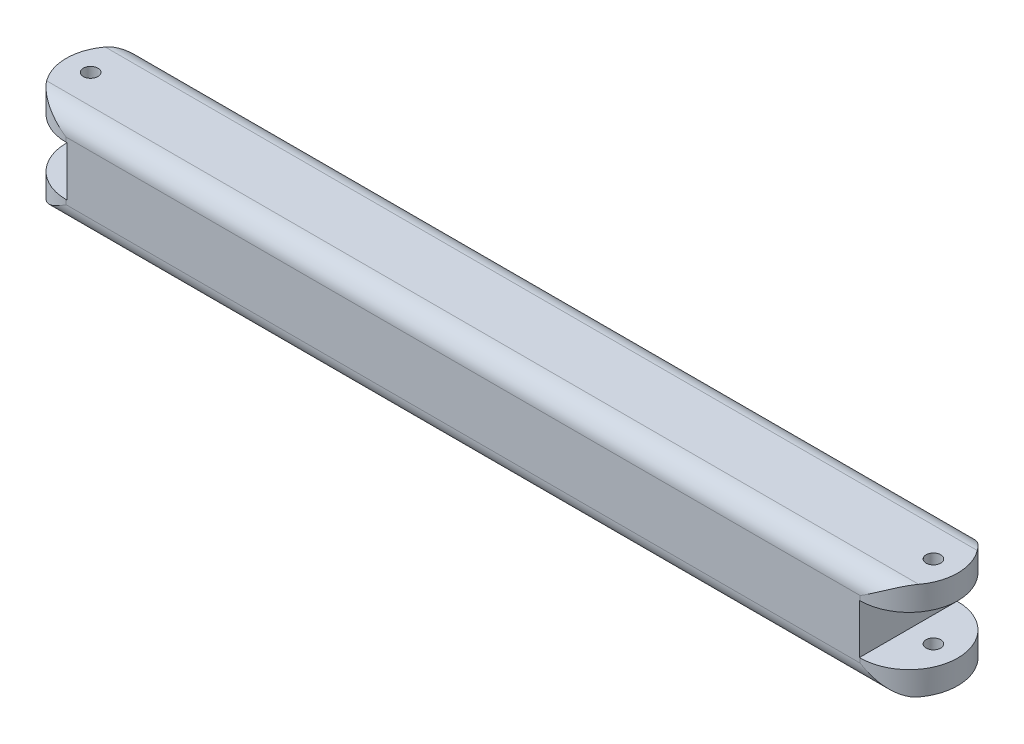
SolidWorks part; units mm, degrees
material "Custom Plastic"
ref_plane "Front Plane" through (0, 0, 0) normal (0, 0, 1) x (1, 0, 0)
ref_plane "Top Plane" through (0, 0, 0) normal (0, 1, 0) x (1, 0, 0)
ref_plane "Right Plane" through (0, 0, 0) normal (1, 0, 0) x (0, 0, -1)
sketch "Sketch1" plane through (0, 0, 0) normal (1, 0, 0) x (0, 0, -1)
  line L0 (-15, 15) -> (15, -15) construction
  line L1 (-15, 25) -> (15, 25)
  line L2 (-25, 15) -> (-25, -15)
  line L3 (-15, -25) -> (15, -25)
  line L4 (25, 15) -> (25, -15)
  arc A1 (-25, -15) -> (-15, -25) centre (-15, -15) ccw
  arc A2 (15, -25) -> (25, -15) centre (15, -15) ccw
  arc A3 (15, 25) -> (25, 15) centre (15, 15) cw
  arc A4 (-15, 25) -> (-25, 15) centre (-15, 15) ccw
  dimension "D2" = 10
  dimension "D3" = 50
extrude "Boss-Extrude1" add sketch "Sketch1" along normal mid plane 456.8
sketch "Sketch2" plane through (0, 0, 0) normal (0, 0, 1) x (1, 0, 0)
  line L0 (0, 0) -> (203, 0) construction
  line L1 (203, 12.7) -> (228.4, 12.7)
  line L2 (203, 12.7) -> (203, -12.7)
  line L3 (203, -12.7) -> (228.4, -12.7)
  line L4 (228.4, 12.7) -> (228.4, -12.7)
  line L5 (-228.4, 12.7) -> (-203, 12.7)
  line L6 (-228.4, 12.7) -> (-228.4, -12.7)
  line L7 (-228.4, -12.7) -> (-203, -12.7)
  line L8 (-203, 12.7) -> (-203, -12.7)
  line L9 (0, 0) -> (-203, 0) construction
  dimension "D1" = 456.8
  dimension "D2" = 25.4
extrude "Cut-Extrude1" cut sketch "Sketch2" against normal mid plane 50
sketch "Sketch4" plane through (0, 0, 0) normal (0, 1, 0) x (1, 0, 0)
  line L0 (-203.4, 0) -> (0, 0) construction
  line L1 (0, 0) -> (203.4, 0) construction
  line L2 (-203.4, 25) -> (-203.4, 45)
  line L3 (-203.4, -25) -> (-203.4, -45)
  line L4 (203.4, 45) -> (203.4, 25)
  line L5 (203.4, -25) -> (203.4, -45)
  line L6 (-203.4, 0) -> (-228.4, 0) construction
  line L7 (203.4, 0) -> (228.4, 0) construction
  arc A0 (-203.4, 25) -> (-203.4, -25) centre (-203.4, 0) ccw
  arc A1 (203.4, 25) -> (203.4, -25) centre (203.4, 0) cw
  arc A2 (-203.4, 45) -> (-203.4, -45) centre (-203.4, 0) ccw
  arc A3 (203.4, 45) -> (203.4, -45) centre (203.4, 0) cw
  circle A4 centre (-215.9, 0) radius 3.75
  circle A5 centre (215.9, 0) radius 3.75
  point P3 (228.4, 0)
  point P7 (-228.4, 0)
  point P22 (0, 0)
  point P23 (0, 0)
  dimension "D1" = 25
  dimension "D5" = 7.5
  dimension "D2" = 456.8
  dimension "D6" = 12.5
  dimension "D3" = 20
  dimension "D4" = 20
extrude "Cut-Extrude6" cut sketch "Sketch4" against normal mid plane 50
equation "\"AxleDiameter\"=0.05"
equation "\"AxleLength\" = 0.3556 + 2 * 0.0506m"
equation "\"D1@Sketch2\"=\"AxleLength\""
equation "\"WheelLinkLength\"=0.0254"
equation "\"D2@Sketch2\"=\"WheelLinkLength\""
equation "\"D1@Cut-Extrude1\"=\"AxleDiameter\""
equation "\"AxleSide\"=0.05"
equation "\"D3@Sketch1\"= \"AxleSide\""
equation "\"D1@Sketch4\"=\"AxleSide\"/2"
equation "\"D2@Sketch4\"=\"AxleLength\""
equation "\"D1@Cut-Extrude6\"=\"AxleSide\""
equation "\"D1@Boss-Extrude1\"=\"AxleLength\""
